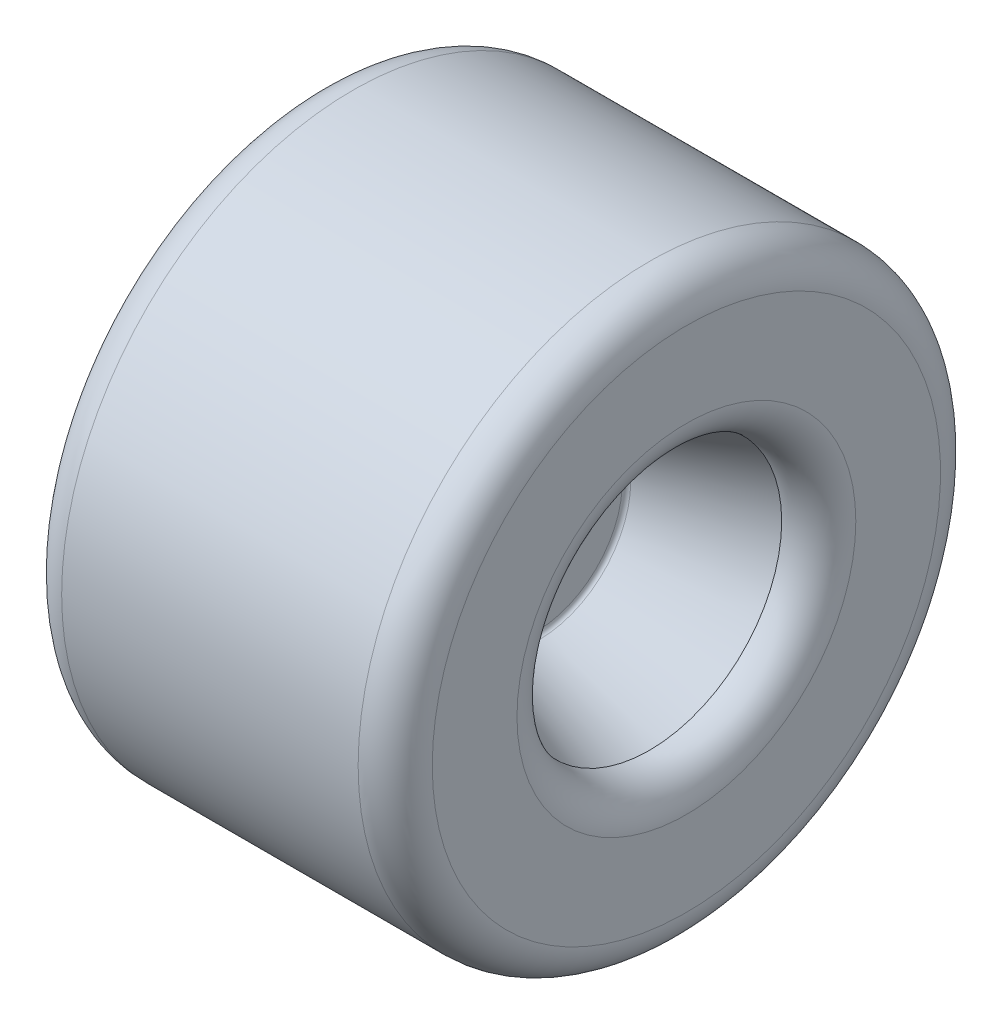
SolidWorks part; units mm, degrees
ref_plane "Front Plane" through (0, 0, 0) normal (0, 0, 1) x (1, 0, 0)
ref_plane "Top Plane" through (0, 0, 0) normal (0, 1, 0) x (1, 0, 0)
ref_plane "Right Plane" through (0, 0, 0) normal (1, 0, 0) x (0, 0, -1)
sketch "Sketch1" plane through (0, 0, 0) normal (0, 0, 1) x (1, 0, 0)
  line L0 (0, 0) -> (0, 139.7) construction
  line L2 (-71.12, 139.7) -> (71.12, 139.7)
  line L3 (-88.9, 121.92) -> (-88.9, 81.28)
  line L5 (88.9, 121.92) -> (88.9, 81.28)
  line L8 (-71.12, 63.5) -> (-71.12, 0) construction
  line L10 (71.12, 63.5) -> (71.12, 0) construction
  line L11 (71.12, 63.5) -> (16.51, 43.4261)
  line L14 (-71.12, 63.5) -> (3.7967, 43.4261)
  line L15 (3.7967, 43.4261) -> (3.7967, 0)
  line L16 (3.7967, 0) -> (16.51, 0)
  line L17 (16.51, 0) -> (16.51, 43.4261)
  arc A0 (71.12, 63.5) -> (88.9, 81.28) centre (71.12, 81.28) ccw
  arc A1 (71.12, 139.7) -> (88.9, 121.92) centre (71.12, 121.92) cw
  arc A2 (-88.9, 81.28) -> (-71.12, 63.5) centre (-71.12, 81.28) ccw
  arc A3 (-71.12, 139.7) -> (-88.9, 121.92) centre (-71.12, 121.92) ccw
  point P12 (88.9, 139.7)
  point P17 (-88.9, 139.7)
  dimension "D4" = 17.78
  dimension "D7" = 3.7967
  dimension "D1" = 177.8
  dimension "D2" = 139.7
  dimension "D5" = 16.51
  dimension "D6" = 63.5
  dimension "D8" = 105
sketch "Sketch3" plane through (0, 0, 0) normal (1, 0, 0) x (0, 0, -1)
  circle A0 centre (0, 0) radius 21.59
  dimension "D1" = 43.18
revolve "Revolve2" add sketch "Sketch1" angle 360 about L16
extrude "Cut-Extrude2" cut sketch "Sketch3" against normal through all both and the other way through all
sketch "Sketch4" plane through (0, 0, 0) normal (1, 0, 0) x (0, 0, -1)
  circle A0 centre (31.75, 0) radius 5
  circle A1 centre (-15.875, -27.4963) radius 5
  circle A2 centre (-15.875, 27.4963) radius 5
  point P9 (0, 0)
  dimension "D1" = 31.75
  dimension "D2" = 10
  dimension "D3" = 3
extrude "Cut-Extrude3" cut sketch "Sketch4" against normal through all both and the other way through all
fillet "Fillet1" radius 2.54 2 edges at (16.51, 0, 43.4261) (3.7967, 0, 43.4261)
